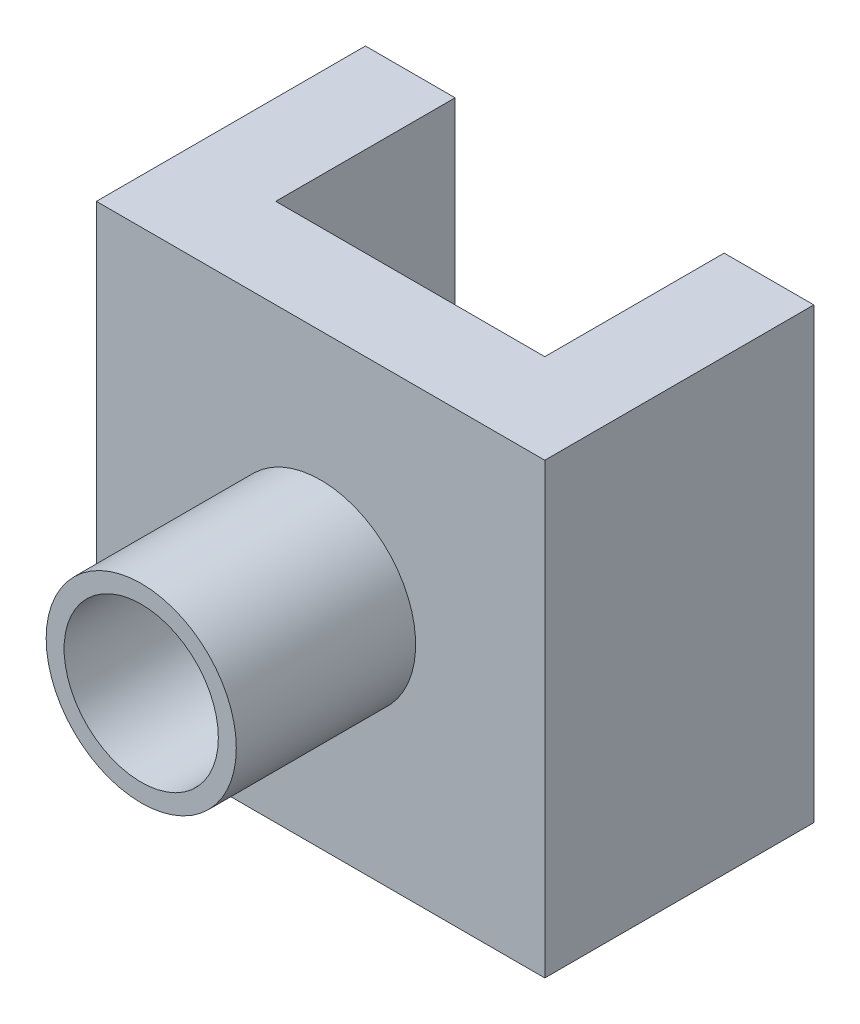
SolidWorks part; units mm, degrees
ref_plane "Front Plane" through (0, 0, 0) normal (0, 0, 1) x (1, 0, 0)
ref_plane "Top Plane" through (0, 0, 0) normal (0, 1, 0) x (1, 0, 0)
ref_plane "Right Plane" through (0, 0, 0) normal (1, 0, 0) x (0, 0, -1)
sketch "Sketch1" plane through (0, 0, 0) normal (0, 0, 1) x (1, 0, 0)
  line L1 (0, 0) -> (25, 0)
  line L2 (0, 0) -> (0, 25)
  line L3 (0, 25) -> (25, 25)
  line L4 (25, 0) -> (25, 25)
  line L5 (0, 0) -> (25, 25) construction
  line L6 (0, 25) -> (25, 0) construction
  point P4 (12.5, 12.5)
  dimension "D1" = 25
  dimension "D2" = 25
extrude "Boss-Extrude1" add sketch "Sketch1" along normal blind 15
sketch "Sketch2" plane through (0, 0, 15) normal (0, 0, 1) x (1, 0, 0)
  line L0 (25, 0) -> (25, 25) construction
  line L1 (0, 25) -> (0, 0) construction
  line L2 (25, 25) -> (0, 25) construction
  circle A1 centre (12.5, 12.5) radius 4.3
  dimension "D1" = 12.5
  dimension "D2" = 25
  dimension "D3" = 12.5
extrude "Cut-Extrude1" cut sketch "Sketch2" against normal through all
sketch "Sketch3" plane through (0, 0, 15) normal (0, 0, 1) x (1, 0, 0)
  line L1 (0, 25) -> (0, 0) construction
  line L2 (0, 0) -> (25, 0) construction
  circle A0 centre (12.5, 12.5) radius 5.3
  circle A2 centre (12.5, 12.5) radius 4.3
  dimension "D1" = 10.6
  dimension "D2" = 12.5
  dimension "D3" = 12.5
extrude "Boss-Extrude2" add sketch "Sketch3" along normal blind 10
sketch "Sketch4" plane through (0, 25, 0) normal (0, 1, 0) x (1, 0, 0)
  line L0 (-13.75, 0) -> (13.75, 0) construction
  line L1 (5, 0) -> (20, 0)
  line L2 (5, 0) -> (5, -10)
  line L3 (5, -10) -> (20, -10)
  line L4 (20, 0) -> (20, -10)
  line L5 (0, -15) -> (0, 0) construction
  line L6 (25, -15) -> (25, 0) construction
  line L7 (25, -15) -> (0, -15) construction
  dimension "D1" = 5
  dimension "D2" = 5
  dimension "D3" = 5
extrude "Cut-Extrude2" cut sketch "Sketch4" against normal blind 28
